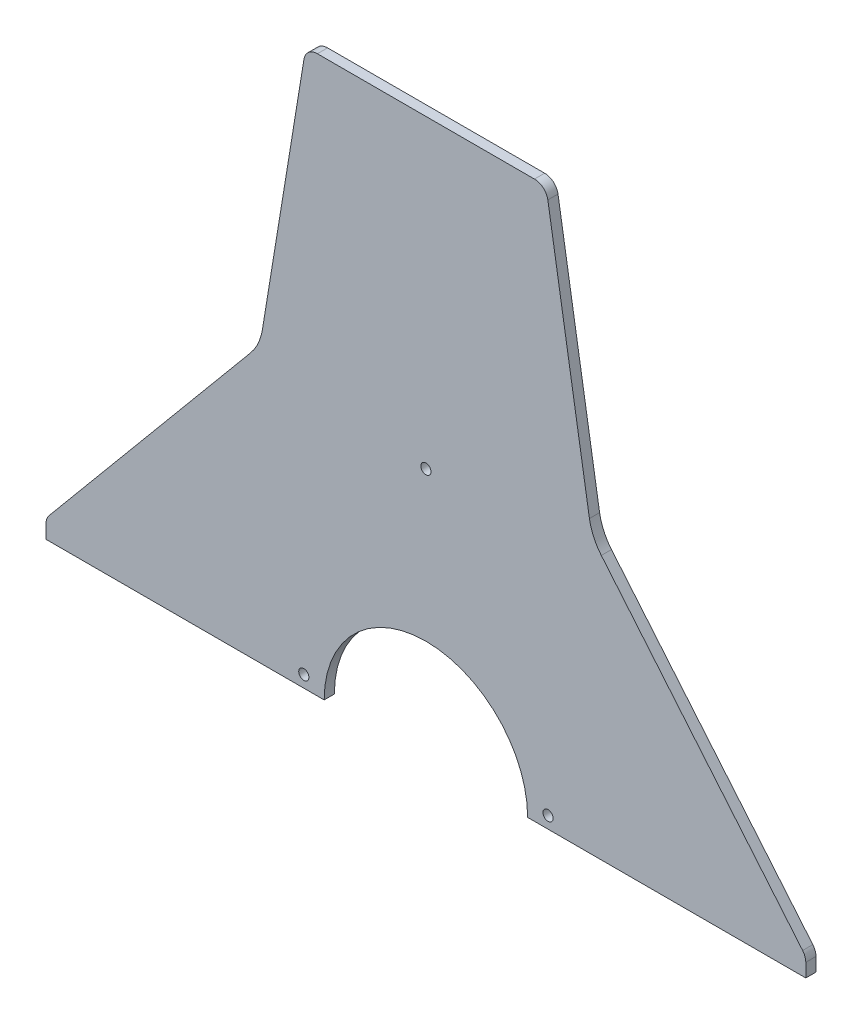
SolidWorks part; units mm, degrees
ref_plane "front" through (0, 0, 0) normal (0, 0, 1) x (1, 0, 0)
ref_plane "top" through (0, 0, 0) normal (0, 1, 0) x (1, 0, 0)
ref_plane "right" through (0, 0, 0) normal (1, 0, 0) x (0, 0, -1)
sketch "Sketch2" plane through (0, 0, 0) normal (1, 0, 0) x (0, 0, -1)
  line L0 (0, 0) -> (0, 660.4) construction
  line L1 (0, 660.4) -> (-130.175, 660.4) construction
  dimension "D1" = 660.4
  dimension "D2" = 130.175
ref_plane "Plane1" through (0, 660.4, 130.175) normal (0, 0, 1) x (1, 0, 0)
sketch "Sketch1" plane through (0, 0, 130.175) normal (0, 0, 1) x (1, 0, 0)
  line L0 (-114.1346, 649.7431) -> (-153.0617, 410.9274)
  line L1 (101.6, 660.4) -> (-101.6, 660.4)
  line L2 (-164.1836, 386.5676) -> (-352.6541, 160.5331)
  line L3 (114.1346, 649.7431) -> (153.0617, 410.9274)
  line L4 (355.6, 152.4) -> (355.6, 139.7)
  line L5 (164.1836, 386.5676) -> (352.6541, 160.5331)
  line L6 (-355.6, 152.4) -> (-355.6, 139.7)
  line L7 (355.6, 139.7) -> (95.25, 139.7)
  line L8 (0, 139.7) -> (0, 317.5) construction
  line L10 (-95.25, 139.7) -> (-355.6, 139.7)
  arc A0 (355.6, 152.4) -> (352.6541, 160.5331) centre (342.9, 152.4) ccw
  arc A1 (-355.6, 152.4) -> (-352.6541, 160.5331) centre (-342.9, 152.4) cw
  arc A2 (101.6, 660.4) -> (114.1346, 649.7431) centre (101.6, 647.7) cw
  arc A3 (-114.1346, 649.7431) -> (-101.6, 660.4) centre (-101.6, 647.7) cw
  arc A4 (153.0617, 410.9274) -> (164.1836, 386.5676) centre (203.2, 419.1) ccw
  arc A5 (-153.0617, 410.9274) -> (-164.1836, 386.5676) centre (-203.2, 419.1) cw
  arc A6 (95.25, 139.7) -> (-95.25, 139.7) centre (0, 139.7) ccw
  point P10 (0, 660.4)
  dimension "D4" = 12.7
  dimension "D5" = 50.8
  dimension "D14" = 95.25
  dimension "D2" = 139.7
  dimension "D3" = 711.2
  dimension "D6" = 12.7
  dimension "D7" = 279.4
  dimension "D8" = 50.178
  dimension "D9" = 99.258
  dimension "D10" = 149.436
  dimension "D11" = 520.7
  dimension "D12" = 203.2
  dimension "D13" = 101.6
  dimension "D15" = 228.2691
  dimension "D16" = 355.6
extrude "Base-Extrude" add sketch "Sketch1" along normal blind 9.525
sketch "Sketch4" plane through (0, 0, 139.7) normal (0, 0, 1) x (1, 0, 0)
  line L0 (95.25, 139.7) -> (355.6, 139.7) construction
  line L1 (0, 0) -> (0, 88.9) construction
  circle A0 centre (0, 374.65) radius 4.7625
  circle A1 centre (114.3, 150.8252) radius 4.7625
  circle A2 centre (-114.3, 150.8252) radius 4.7625
  dimension "D1" = 9.525
  dimension "D2" = 234.95
  dimension "D3" = 11.1252
  dimension "D4" = 114.3
extrude "Cut-Extrude1" cut sketch "Sketch4" against normal through all
